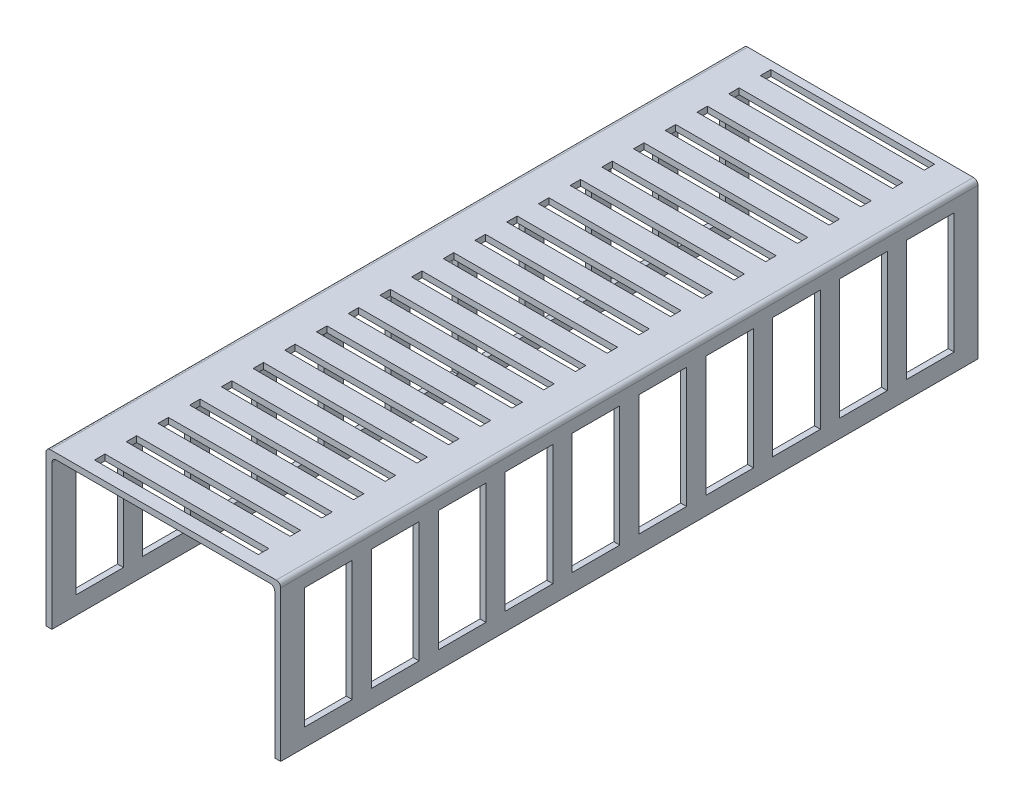
SolidWorks part; units mm, degrees
material "Nylon 101"
ref_plane "Front Plane" through (0, 0, 0) normal (0, 0, 1) x (1, 0, 0)
ref_plane "Top Plane" through (0, 0, 0) normal (0, 1, 0) x (1, 0, 0)
ref_plane "Right Plane" through (0, 0, 0) normal (1, 0, 0) x (0, 0, -1)
sketch "Sketch2" plane through (0, 26475.0493, 0) normal (0, 1, 0) x (1, 0, 0)
  line L0 (-34.7, 120.7548) -> (-34.7, 117.2548)
  line L5 (-34.7, 117.2548) -> (20.3, 117.2548)
  line L6 (-34.7, 120.7548) -> (20.3, 120.7548)
  line L7 (20.3, 120.7548) -> (20.3, 117.2548)
  line L9 (-46.6, 134.05) -> (32.2, 134.05)
  line L10 (-46.6, 134.05) -> (-46.6, -100.05)
  line L11 (-46.6, -100.05) -> (32.2, -100.05)
  line L12 (32.2, 134.05) -> (32.2, -100.05)
  line L13 (-49.2, -101.05) -> (34.8, -101.05) construction
  line L17 (33.2179, 129.65) -> (30.05, 129.65) construction
  line L18 (30.05, 124.75) -> (30.05, 130.7) construction
  line L19 (-38.7, 139.3) -> (-38.7, 131.4) construction
  line L20 (-34.7, 131.4) -> (20.3, 131.4)
  line L21 (-34.7, 131.4) -> (-34.7, 127.9)
  line L22 (-34.7, 127.9) -> (20.3, 127.9)
  line L23 (20.3, 131.4) -> (20.3, 127.9)
  line L24 (-34.7, 131.4) -> (20.3, 127.9) construction
  line L25 (-34.7, 127.9) -> (20.3, 131.4) construction
  line L26 (-34.7, 110.1095) -> (-34.7, 106.6095)
  line L27 (-34.7, 106.6095) -> (20.3, 106.6095)
  line L28 (-34.7, 110.1095) -> (20.3, 110.1095)
  line L29 (20.3, 110.1095) -> (20.3, 106.6095)
  line L30 (-34.7, 99.4643) -> (-34.7, 95.9643)
  line L31 (-34.7, 95.9643) -> (20.3, 95.9643)
  line L32 (-34.7, 99.4643) -> (20.3, 99.4643)
  line L33 (20.3, 99.4643) -> (20.3, 95.9643)
  line L34 (-34.7, 88.819) -> (-34.7, 85.319)
  line L35 (-34.7, 85.319) -> (20.3, 85.319)
  line L36 (-34.7, 88.819) -> (20.3, 88.819)
  line L37 (20.3, 88.819) -> (20.3, 85.319)
  line L38 (-34.7, 78.1738) -> (-34.7, 74.6738)
  line L39 (-34.7, 74.6738) -> (20.3, 74.6738)
  line L40 (-34.7, 78.1738) -> (20.3, 78.1738)
  line L41 (20.3, 78.1738) -> (20.3, 74.6738)
  line L42 (-34.7, 67.5286) -> (-34.7, 64.0286)
  line L43 (-34.7, 64.0286) -> (20.3, 64.0286)
  line L44 (-34.7, 67.5286) -> (20.3, 67.5286)
  line L45 (20.3, 67.5286) -> (20.3, 64.0286)
  line L46 (-34.7, 56.8833) -> (-34.7, 53.3833)
  line L47 (-34.7, 53.3833) -> (20.3, 53.3833)
  line L48 (-34.7, 56.8833) -> (20.3, 56.8833)
  line L49 (20.3, 56.8833) -> (20.3, 53.3833)
  line L50 (-34.7, 46.2381) -> (-34.7, 42.7381)
  line L51 (-34.7, 42.7381) -> (20.3, 42.7381)
  line L52 (-34.7, 46.2381) -> (20.3, 46.2381)
  line L53 (20.3, 46.2381) -> (20.3, 42.7381)
  line L54 (-34.7, 35.5929) -> (-34.7, 32.0929)
  line L55 (-34.7, 32.0929) -> (20.3, 32.0929)
  line L56 (-34.7, 35.5929) -> (20.3, 35.5929)
  line L57 (20.3, 35.5929) -> (20.3, 32.0929)
  line L58 (-34.7, 24.9476) -> (-34.7, 21.4476)
  line L59 (-34.7, 21.4476) -> (20.3, 21.4476)
  line L60 (-34.7, 24.9476) -> (20.3, 24.9476)
  line L61 (20.3, 24.9476) -> (20.3, 21.4476)
  line L62 (-34.7, 14.3024) -> (-34.7, 10.8024)
  line L63 (-34.7, 10.8024) -> (20.3, 10.8024)
  line L64 (-34.7, 14.3024) -> (20.3, 14.3024)
  line L65 (20.3, 14.3024) -> (20.3, 10.8024)
  line L66 (-34.7, 3.6571) -> (-34.7, 0.1571)
  line L67 (-34.7, 0.1571) -> (20.3, 0.1571)
  line L68 (-34.7, 3.6571) -> (20.3, 3.6571)
  line L69 (20.3, 3.6571) -> (20.3, 0.1571)
  line L70 (-34.7, -6.9881) -> (-34.7, -10.4881)
  line L71 (-34.7, -10.4881) -> (20.3, -10.4881)
  line L72 (-34.7, -6.9881) -> (20.3, -6.9881)
  line L73 (20.3, -6.9881) -> (20.3, -10.4881)
  line L74 (-34.7, -17.6333) -> (-34.7, -21.1333)
  line L75 (-34.7, -21.1333) -> (20.3, -21.1333)
  line L76 (-34.7, -17.6333) -> (20.3, -17.6333)
  line L77 (20.3, -17.6333) -> (20.3, -21.1333)
  line L78 (-34.7, -28.2786) -> (-34.7, -31.7786)
  line L79 (-34.7, -31.7786) -> (20.3, -31.7786)
  line L80 (-34.7, -28.2786) -> (20.3, -28.2786)
  line L81 (20.3, -28.2786) -> (20.3, -31.7786)
  line L82 (-34.7, -38.9238) -> (-34.7, -42.4238)
  line L83 (-34.7, -42.4238) -> (20.3, -42.4238)
  line L84 (-34.7, -38.9238) -> (20.3, -38.9238)
  line L85 (20.3, -38.9238) -> (20.3, -42.4238)
  line L86 (-34.7, -49.569) -> (-34.7, -53.069)
  line L87 (-34.7, -53.069) -> (20.3, -53.069)
  line L88 (-34.7, -49.569) -> (20.3, -49.569)
  line L89 (20.3, -49.569) -> (20.3, -53.069)
  line L90 (-34.7, -60.2143) -> (-34.7, -63.7143)
  line L91 (-34.7, -63.7143) -> (20.3, -63.7143)
  line L92 (-34.7, -60.2143) -> (20.3, -60.2143)
  line L93 (20.3, -60.2143) -> (20.3, -63.7143)
  line L94 (-34.7, -70.8595) -> (-34.7, -74.3595)
  line L95 (-34.7, -74.3595) -> (20.3, -74.3595)
  line L96 (-34.7, -70.8595) -> (20.3, -70.8595)
  line L97 (20.3, -70.8595) -> (20.3, -74.3595)
  line L98 (-34.7, -81.5048) -> (-34.7, -85.0048)
  line L99 (-34.7, -85.0048) -> (20.3, -85.0048)
  line L100 (-34.7, -81.5048) -> (20.3, -81.5048)
  line L101 (20.3, -81.5048) -> (20.3, -85.0048)
  line L102 (-34.7, -92.15) -> (-34.7, -95.65)
  line L103 (-34.7, -95.65) -> (20.3, -95.65)
  line L104 (-34.7, -92.15) -> (20.3, -92.15)
  line L105 (20.3, -92.15) -> (20.3, -95.65)
  line L107 (-49.2, 135.05) -> (34.8, 135.05) construction
  line L108 (-47.2, -100.65) -> (-47.2, 134.65) construction
  line L109 (32.8, -100.65) -> (32.8, 134.65) construction
  point P21 (-7.2, 129.65)
  dimension "D1" = 1
  dimension "D2" = 1
  dimension "D3" = 0.6
  dimension "D4" = 0.6
  dimension "D5" = 4
  dimension "D6" = 3.5
  dimension "D8" = 4.4
  dimension "D9" = 4.4
  dimension "D7" = 22
extrude "Boss-Extrude1" add sketch "Sketch2" along normal blind 2
sketch "Sketch3" plane through (0, 26475.0493, 0) normal (0, -1, 0) x (1, 0, 0)
  line L0 (32.2, -134.05) -> (-46.6, -134.05) construction
  line L1 (-46.6, 100.05) -> (-44.6, 100.05)
  line L2 (-46.6, 100.05) -> (-46.6, -134.05)
  line L3 (-46.6, -134.05) -> (-44.6, -134.05)
  line L4 (-44.6, 100.05) -> (-44.6, -134.05)
  line L5 (-7.2, 100.05) -> (-7.2, -2.7153) construction
  line L6 (-46.6, 100.05) -> (32.2, 100.05) construction
  line L7 (30.2, 100.05) -> (30.2, -134.05)
  line L8 (32.2, -134.05) -> (30.2, -134.05)
  line L9 (32.2, 100.05) -> (32.2, -134.05)
  line L10 (32.2, 100.05) -> (30.2, 100.05)
  dimension "D1" = 2
extrude "Boss-Extrude2" add sketch "Sketch3" along normal blind 50
fillet "Fillet1" radius 1.5 4 edges at (-44.6, 26475.0493, -17) (-46.6, 26477.0493, -17) (30.2, 26475.0493, -17) (32.2, 26477.0493, -17)
sketch "Sketch4" plane through (32.2, 0, 0) normal (1, 0, 0) x (0, 0, -1)
  line L0 (-100.05, 26475.5493) -> (-100.05, 26425.0493) construction
  line L1 (-92.05, 26471.5493) -> (-76.05, 26471.5493)
  line L2 (-92.05, 26471.5493) -> (-92.05, 26431.0493)
  line L3 (-92.05, 26431.0493) -> (-76.05, 26431.0493)
  line L4 (-76.05, 26471.5493) -> (-76.05, 26431.0493)
  line L5 (134.05, 26475.5493) -> (-100.05, 26475.5493) construction
  line L6 (134.05, 26425.0493) -> (-100.05, 26425.0493) construction
  line L7 (-69.5944, 26471.5493) -> (-53.5944, 26471.5493)
  line L8 (-69.5944, 26471.5493) -> (-69.5944, 26431.0493)
  line L9 (-69.5944, 26431.0493) -> (-53.5944, 26431.0493)
  line L10 (-53.5944, 26471.5493) -> (-53.5944, 26431.0493)
  line L11 (-47.1389, 26471.5493) -> (-31.1389, 26471.5493)
  line L12 (-47.1389, 26471.5493) -> (-47.1389, 26431.0493)
  line L13 (-47.1389, 26431.0493) -> (-31.1389, 26431.0493)
  line L14 (-31.1389, 26471.5493) -> (-31.1389, 26431.0493)
  line L15 (-24.6833, 26471.5493) -> (-8.6833, 26471.5493)
  line L16 (-24.6833, 26471.5493) -> (-24.6833, 26431.0493)
  line L17 (-24.6833, 26431.0493) -> (-8.6833, 26431.0493)
  line L18 (-8.6833, 26471.5493) -> (-8.6833, 26431.0493)
  line L19 (-2.2278, 26471.5493) -> (13.7722, 26471.5493)
  line L20 (-2.2278, 26471.5493) -> (-2.2278, 26431.0493)
  line L21 (-2.2278, 26431.0493) -> (13.7722, 26431.0493)
  line L22 (13.7722, 26471.5493) -> (13.7722, 26431.0493)
  line L23 (20.2278, 26471.5493) -> (36.2278, 26471.5493)
  line L24 (20.2278, 26471.5493) -> (20.2278, 26431.0493)
  line L25 (20.2278, 26431.0493) -> (36.2278, 26431.0493)
  line L26 (36.2278, 26471.5493) -> (36.2278, 26431.0493)
  line L27 (42.6833, 26471.5493) -> (58.6833, 26471.5493)
  line L28 (42.6833, 26471.5493) -> (42.6833, 26431.0493)
  line L29 (42.6833, 26431.0493) -> (58.6833, 26431.0493)
  line L30 (58.6833, 26471.5493) -> (58.6833, 26431.0493)
  line L31 (65.1389, 26471.5493) -> (81.1389, 26471.5493)
  line L32 (65.1389, 26471.5493) -> (65.1389, 26431.0493)
  line L33 (65.1389, 26431.0493) -> (81.1389, 26431.0493)
  line L34 (81.1389, 26471.5493) -> (81.1389, 26431.0493)
  line L35 (87.5944, 26471.5493) -> (103.5944, 26471.5493)
  line L36 (87.5944, 26471.5493) -> (87.5944, 26431.0493)
  line L37 (87.5944, 26431.0493) -> (103.5944, 26431.0493)
  line L38 (103.5944, 26471.5493) -> (103.5944, 26431.0493)
  line L39 (110.05, 26471.5493) -> (126.05, 26471.5493)
  line L40 (110.05, 26471.5493) -> (110.05, 26431.0493)
  line L41 (110.05, 26431.0493) -> (126.05, 26431.0493)
  line L42 (126.05, 26471.5493) -> (126.05, 26431.0493)
  line L43 (134.05, 26475.5493) -> (134.05, 26425.0493) construction
  dimension "D1" = 8
  dimension "D2" = 4
  dimension "D3" = 6
  dimension "D4" = 16
  dimension "D6" = 8
  dimension "D5" = 10
extrude "Cut-Extrude1" cut sketch "Sketch4" against normal through all
